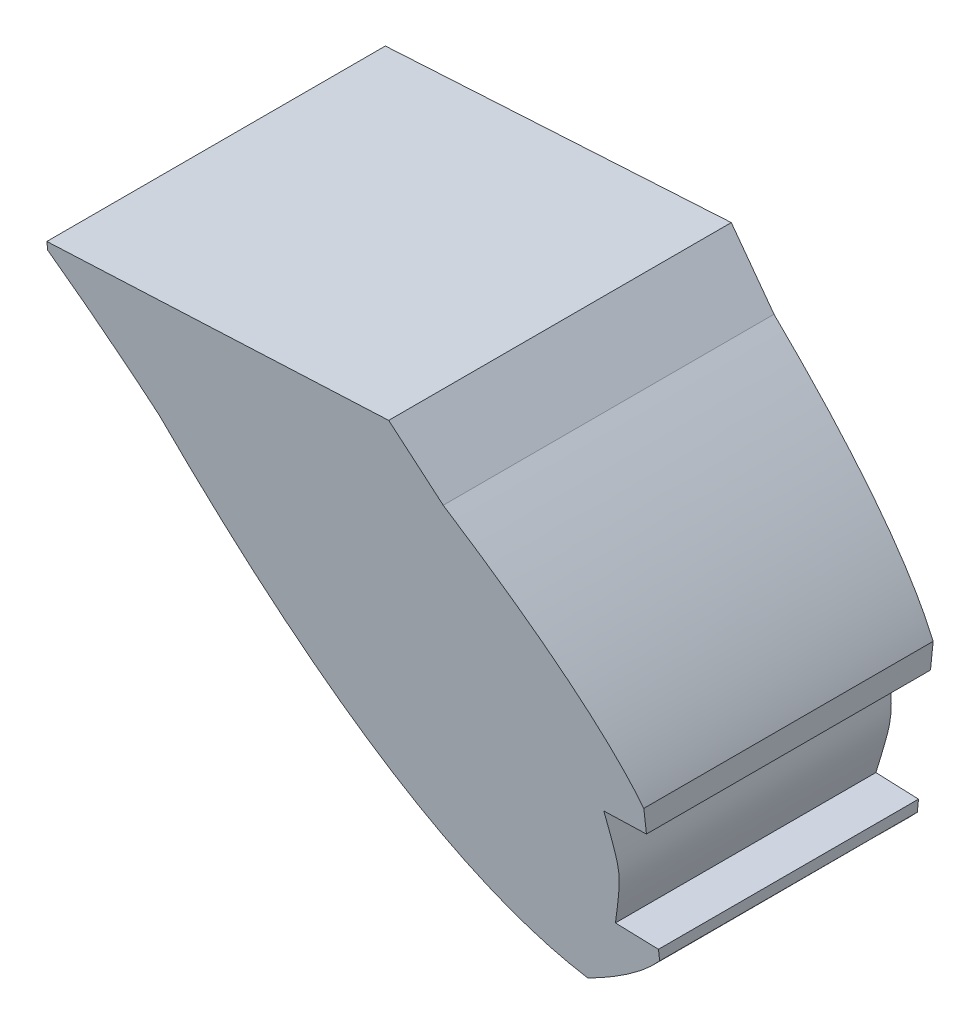
SolidWorks part; units mm, degrees
ref_plane "Alzado" through (0, 0, 0) normal (0, 0, 1) x (1, 0, 0)
ref_plane "Planta" through (0, 0, 0) normal (0, 1, 0) x (1, 0, 0)
ref_plane "Vista lateral" through (0, 0, 0) normal (1, 0, 0) x (0, 0, -1)
sketch "Croquis1" plane through (0, 0, 0) normal (0, 0, 1) x (1, 0, 0)
  line L0 (-8.9818, 12.6082) -> (-23.0359, 11.8716) construction
  line L1 (-8.9818, 12.6082) -> (-23.0359, 11.8716)
  line L2 (-8.9818, 12.6082) -> (-23.0359, 11.8716) construction
  line L4 (-8.9818, 12.6082) -> (-23.0359, 11.8716)
  line L6 (-1.3949, 1.9763) -> (0.3551, 2.2848) construction
  line L7 (-1.3949, 1.9763) -> (0.3551, 2.2848)
  line L8 (0.3551, 2.2848) -> (0.3551, 2.8423) construction
  line L9 (0.3551, 2.2848) -> (0.3551, 3.0015)
  line L10 (0.3551, -2.2848) -> (-1.3949, -2.2237) construction
  line L11 (0.3551, -2.2848) -> (-1.3949, -2.2237)
  line L12 (0.3551, 2.2848) -> (0.3551, -2.2848) construction
  line L13 (0.3551, -2.2848) -> (0.3551, -2.7233)
  line L14 (-8.9818, 12.6082) -> (-6.9949, 10.4774)
  line L15 (-23.0359, 11.5401) -> (-23.0359, 11.8716) construction
  line L16 (-23.0359, 11.5401) -> (-23.0359, 11.8716)
  arc A0 (-18.9452, 7.5409) -> (-23.0359, 11.5401) centre (-69.8841, -40.4718) ccw construction
  arc A1 (-18.9452, 7.5409) -> (-23.0359, 11.5401) centre (-69.8841, -40.4718) ccw
  spline S1 degree 2 poles (-828.7061, 3922.2202) (545.889, -3962.7836) (-262.0834, 3982.5902) knots 0.462185 0.462185 0.462185 0.537731 0.537731 0.537731 weights 1 1 1 only from (-18.9452, 7.5409) to (-2.8466, -5.0591) construction
  spline S2 degree 2 poles (-18.9452, 7.5409) (-10.215, -3.6976) (-2.8466, -5.0591) knots 0.497667 0.497667 0.497667 0.499554 0.499554 0.499554 weights 1 1 1
  spline S3 degree 2 poles (-3804.8689, 1232.5771) (3762.9122, -1369.6643) (-3716.5752, 1504.852) knots 0.462212 0.462212 0.462212 0.537836 0.537836 0.537836 weights 1 1 1 only from (0.3551, 3.0015) to (-6.9949, 10.4774) construction
  spline S4 degree 2 poles (0.3551, 3.0015) (-1.4487, 6.0584) (-6.9949, 10.4774) knots 0.500821 0.500821 0.500821 0.502013 0.502013 0.502013 weights 1 1 1
  spline S5 degree 2 poles (-1.3949, -2.2237) (-0.9075, -0.1237) (-1.3949, 1.9763) knots 0 0 0 1 1 1 weights 1 3.231801 1 construction
  spline S6 degree 2 poles (-1.3949, -2.2237) (-0.9075, -0.1237) (-1.3949, 1.9763) knots 0 0 0 1 1 1 weights 1 3.231801 1
  spline S7 degree 2 poles (-3997.263, 185.0077) (3984.2333, -348.7483) (-3965.0625, 511.2595) knots 0.462205 0.462205 0.462205 0.537778 0.537778 0.537778 weights 1 1 1 only from (-2.8466, -5.0591) to (0.3551, -2.7233) construction
  spline S8 degree 2 poles (-2.8466, -5.0591) (-0.7424, -3.9352) (0.3551, -2.7233) knots 0.498812 0.498812 0.498812 0.499413 0.499413 0.499413 weights 1 1 1
extrude "Saliente-Extruir1" add sketch "Croquis1" along normal mid plane 14 contours S2 S8 L13 L11 S6 L7 L9 S4 L14 L1 L16 A1
sketch "Croquis3" plane through (0, 0, 0) normal (0, 0, 1) x (1, 0, 0)
  line L0 (-6.742, 0) -> (0, 0) construction
  line L1 (-1.8181, 2) -> (-1.7771, 2.0103) construction
  line L3 (-1.8181, 2) -> (-0.1689, 2.4155) construction
  line L4 (-1.8181, 2) -> (0.3551, 3.0015)
  line L5 (0.3551, 3.0015) -> (0.3551, 0)
  line L6 (-1.9135, -2.1825) -> (0.3551, -2.2848)
  line L7 (0.3551, -2.2848) -> (0.3551, 0)
  parabola Q0 (-1.9135, -2.1825) -> (-1.8181, 2) focus (-3.3181, 0) apex (-1.3181, 0)
  dimension "D1" = 2
  dimension "D2" = 2
extrude "Cortar-Extruir1" [suppressed] cut sketch "Croquis3" against normal through all both and the other way through all
sketch "Croquis4" plane through (0, 0, 0) normal (0, 0, 1) x (1, 0, 0)
  line L0 (-1.3949, 1.9763) -> (0.3551, 2.2848) construction
  line L1 (-1.3949, 1.9763) -> (0.3551, 2.2848)
  line L2 (0.3551, 2.2848) -> (0.3551, 3.0015) construction
  line L3 (0.3551, 2.0374) -> (0.3551, 2.2848)
  line L4 (-1.3949, 1.9763) -> (0.3551, 2.0374)
  line L5 (0, 0) -> (-3.4665, 0) construction
  dimension "D1" = 2
extrude "Saliente-Extruir2" add sketch "Croquis4" along normal through all and the other way through all
sketch "Croquis7" plane through (0, 0, 0) normal (0, 0, 1) x (1, 0, 0)
  line L0 (0, 0) -> (-15.3945, 3.3171) construction
  line L1 (-17.3963, 18.9371) -> (-15.3945, 3.3171) construction
  line L2 (-15.3945, 3.3171) -> (-9.9316, -2.6296) construction
  line L3 (-15.3945, 3.3171) -> (-10.2385, 8.0535) construction
  line L4 (-17.3963, 18.9371) -> (-16.5429, 12.2783) construction
  line L5 (0, 0) -> (-1.3461, -2.2254) construction
  line L6 (-69.8841, 29.5282) -> (-81.9382, 42.5765) construction
  line L7 (-69.8841, 29.5282) -> (-20.9497, 29.5282) construction
  line L8 (-17.8101, 13.1658) -> (-25.5429, 13.1658)
  line L9 (-18.2059, 7.0951) -> (-21.9246, 11.9299) construction
  line L10 (0.3551, -2.5) -> (-2.4497, -2.0473)
  line L11 (-1.3461, -2.2254) -> (-2.0075, -3.6222) construction
  line L12 (-1.3461, -2.2254) -> (-1.4547, -2.8987) construction
  line L13 (-1.3461, -2.2254) -> (-1.2286, -1.4976) construction
  line L14 (0.3551, -2.2848) -> (0.3551, -2.7233) construction
  line L15 (0.3551, -2.2848) -> (-1.3949, -2.2237) construction
  line L16 (-2.0075, -3.6222) -> (-3.0629, -5.8512) construction
  line L17 (-2.6331, -4.9434) -> (-3.7044, -5.5324) construction
  line L18 (-2.6331, -4.9434) -> (-3.2248, -3.867) construction
  line L19 (-2.6331, -4.9434) -> (-2.2174, -6.1341) construction
  line L20 (-4.0838, -4.7637) -> (-1.6363, -5.0668) construction
  line L21 (-4.0838, -4.7637) -> (-0.036, -5.9454) construction
  line L22 (-4.0838, -4.7637) -> (-3.7621, -3.6616) construction
  line L23 (-4.0838, -4.7637) -> (-6.31, -3.7023) construction
  line L24 (-6.31, -3.7023) -> (-8.69, -2.5677) construction
  line L25 (-8.69, -2.5677) -> (-6.8421, -3.7725) construction
  line L26 (-8.69, -2.5677) -> (-7.9481, -1.4297) construction
  line L27 (-10.6884, -0.8477) -> (-8.69, -2.5677) construction
  line L28 (-10.6884, -0.8477) -> (-14.8546, 2.738) construction
  line L29 (-14.8546, 2.738) -> (-14.5337, 2.3989) construction
  line L30 (-14.8546, 2.738) -> (-14.6199, 2.9602) construction
  line L31 (-18.2059, 7.0951) -> (-14.8546, 2.738) construction
  line L32 (-8.9818, 12.6082) -> (-23.0359, 11.8716) construction
  line L33 (-8.9818, 12.6082) -> (-23.0359, 11.8716)
  line L34 (-21.9246, 11.9299) -> (-21.9826, 13.0367) construction
  line L35 (-21.9246, 11.9299) -> (-23.4156, 13.0367) construction
  arc A0 (-18.9452, 7.5409) -> (-23.0359, 11.5401) centre (-69.8841, -40.4718) ccw construction
  spline S0 degree 2 poles (-654.4568, 2937.5195) (409.3679, -2972.9237) (-163.476, 2987.5518) knots 0.467242 0.467242 0.467242 0.532662 0.532662 0.532662 weights 1 1 1 only from (-18.9452, 7.5409) to (-2.8466, -5.0591) construction
  spline S1 degree 2 poles (-18.6263, 7.1332) (-10.0803, -3.7225) (-2.8466, -5.0591) knots 0.497702 0.497702 0.497702 0.499554 0.499554 0.499554 weights 1 1 1 construction
  spline S3 degree 2 poles (-2999.4042, 119.7504) (2988.2948, -261.6206) (-2971.0465, 402.239) knots 0.467267 0.467267 0.467267 0.532713 0.532713 0.532713 weights 1 1 1 only from (-2.8466, -5.0591) to (0.3551, -2.7233) construction
  spline S4 degree 2 poles (-2.8466, -5.0591) (-2.7385, -5.0013) (-2.6331, -4.9434) knots 0.498812 0.498812 0.498812 0.498843 0.498843 0.498843 weights 1 1 1
  dimension "D1" = 2.5
  dimension "D2" = 22
  dimension "D3" = 16.17
  dimension "D4" = 54.138
  dimension "D5" = 34.566
  dimension "D6" = 50.413
sketch "Croquis6" plane through (0, 0, 0) normal (1, 0, 0) x (0, 0, -1)
  line L0 (7, 12.6082) -> (7, 10.4774) construction
  line L1 (7, 12.6082) -> (7, -5.0591)
  line L2 (-7, 12.6082) -> (-7, 10.4774) construction
  line L3 (-7, 12.6082) -> (-7, -5.0591)
  line L4 (-7, -5.0591) -> (7, -5.0591) construction
  line L5 (-7, -5.0591) -> (-5, -5.0591)
  line L6 (7, 12.6082) -> (5, -5.0591)
  line L7 (-7, 12.6082) -> (-5, -5.0591)
  line L8 (5, -5.0591) -> (7, -5.0591)
  dimension "D1" = 2
  dimension "D2" = 2
extrude "Cortar-Extruir2" cut sketch "Croquis6" against normal through all and the other way through all
